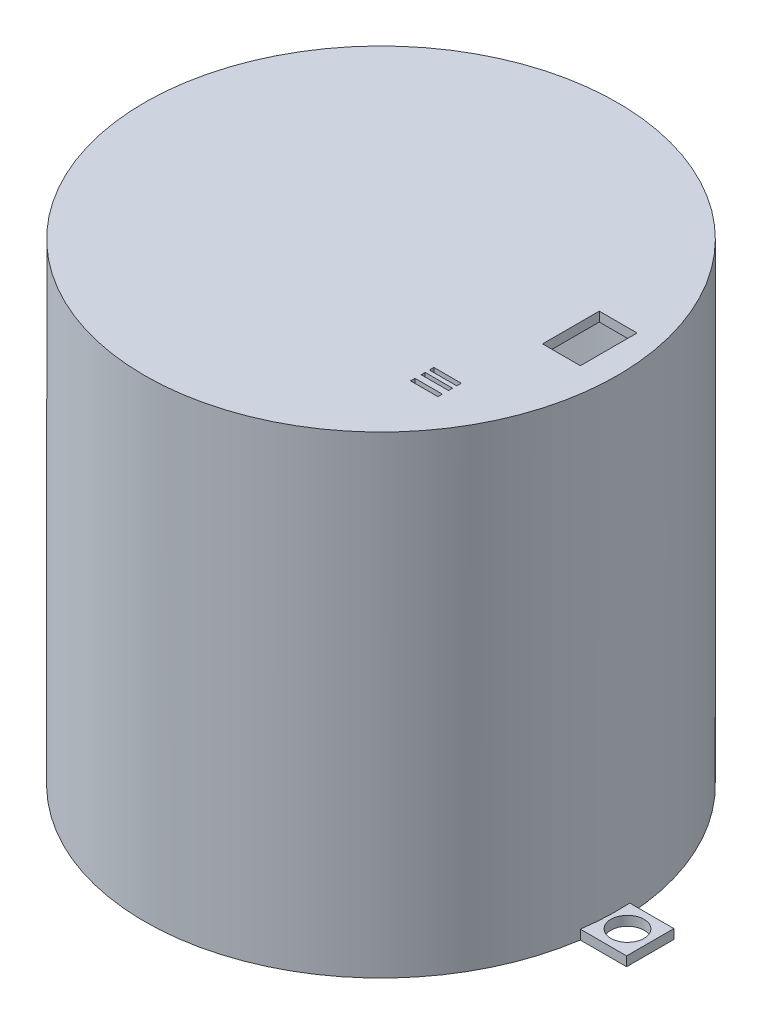
SolidWorks part; units mm, degrees
ref_plane "Front Plane" through (0, 0, 0) normal (0, 0, 1) x (1, 0, 0)
ref_plane "Top Plane" through (0, 0, 0) normal (0, 1, 0) x (1, 0, 0)
ref_plane "Right Plane" through (0, 0, 0) normal (1, 0, 0) x (0, 0, -1)
sketch "Sketch2" plane through (0, 0, 0) normal (0, 1, 0) x (1, 0, 0)
  circle A0 centre (0, 0) radius 50
  dimension "D1" = 100
extrude "Boss-Extrude1" add sketch "Sketch2" along normal blind 100
sketch "Sketch3" plane through (0, 0, 0) normal (1, 0, 0) x (0, 0, -1)
  line L0 (50, 100) -> (-50, 100) construction
  line L5 (-50, 0) -> (50, 0) construction
  line L6 (50, 0) -> (50, 100) construction
  line L7 (-30, 90) -> (30, 90)
  line L8 (-30, 90) -> (-30, 10)
  line L9 (-30, 10) -> (30, 10)
  line L10 (30, 90) -> (30, 10)
  line L11 (-50, 100) -> (-50, 0) construction
  dimension "D1" = 10
  dimension "D2" = 10
  dimension "D3" = 20
  dimension "D4" = 20
extrude "Cut-Extrude1" cut sketch "Sketch3" against normal blind 60
sketch "Sketch4" plane through (0, 0, 0) normal (-1, 0, 0) x (0, 0, 1)
  line L0 (30, 90) -> (30, 10) construction
  line L1 (-30, 10) -> (30, 10)
  line L2 (-30, 10) -> (-30, 89.6698)
  line L3 (-30, 89.6698) -> (30, 89.6698)
  line L4 (30, 10) -> (30, 89.6698)
extrude "Boss-Extrude3" add sketch "Sketch4" along normal blind 40
sketch "Sketch5" plane through (0, 0, 0) normal (0, 1, 0) x (1, 0, 0)
  circle A0 centre (0, 0) radius 38
  dimension "D1" = 76
extrude "Cut-Extrude2" cut sketch "Sketch5" along normal blind 90
sketch "Sketch6" plane through (-40, 0, 0) normal (-1, 0, 0) x (0, 0, 1)
sketch "Sketch8" plane through (-40, 0, 0) normal (-1, 0, 0) x (0, 0, 1)
  line L0 (-30, 10) -> (-30, 89.6698) construction
  line L1 (30, 89.6698) -> (-30, 89.6698)
  line L2 (30, 89.6698) -> (30, 10)
  line L3 (30, 10) -> (-30, 10)
  line L4 (-30, 89.6698) -> (-30, 10)
  line L5 (-30, 10) -> (30, 10) construction
extrude "Cut-Extrude7" cut sketch "Sketch8" against normal blind 50
sketch "Sketch10" plane through (0, 90, 0) normal (0, -1, 0) x (-1, 0, 0)
  circle A0 centre (0, 0) radius 48.6655
extrude "Cut-Extrude9" cut sketch "Sketch10" along normal blind 100
sketch "Sketch11" plane through (0, 90, 0) normal (0, -1, 0) x (1, 0, 0)
  line L1 (-40, -30) -> (-38.3188, -30)
  line L2 (-40, -30) -> (-40, 30)
  line L3 (-40, 30) -> (-38.3188, 30)
  line L4 (-38.3188, -30) -> (-38.3188, 30)
extrude "Boss-Extrude5" add sketch "Sketch11" along normal blind 80
sketch "Sketch13" plane through (0, 10, 0) normal (0, -1, 0) x (1, 0, 0)
  line L2 (-38.3188, -30) -> (-38.3188, 30) construction
  line L3 (-38.3188, 30) -> (-40, 30)
  line L4 (-38.3188, 30) -> (-38.3188, -30)
  line L5 (-38.3188, -30) -> (-40, -30)
  line L6 (-40, 30) -> (-40, -30)
  circle A1 centre (0, 0) radius 48.6655 construction
extrude "Boss-Extrude7" add sketch "Sketch13" along normal blind 10
sketch "Sketch16" plane through (0, 0, 0) normal (0, -1, 0) x (1, 0, 0)
  line L0 (-39.28, -29.0752) -> (-39.28, 29.2384)
  arc A0 (-39.28, -29.0752) -> (-39.28, 29.2384) centre (-2.0923, 0.0816) cw
extrude "Boss-Extrude8" add sketch "Sketch16" against normal blind 10
sketch "Sketch17" plane through (0, 90, 0) normal (0, -1, 0) x (1, 0, 0)
  line L0 (-38.3188, 30) -> (-38.3188, -30)
  arc A0 (-38.3188, -30) -> (-38.3188, 30) centre (0, 0) ccw
extrude "Cut-Extrude10" cut sketch "Sketch17" against normal blind 5
sketch "Sketch19" plane through (0, 95, 0) normal (0, -1, 0) x (-1, 0, 0)
  circle A0 centre (-31.4631, -20.5499) radius 8.1648
extrude "Boss-Extrude10" add sketch "Sketch19" along normal blind 5
sketch "Sketch20" plane through (0, 90, 0) normal (0, -1, 0) x (-1, 0, 0)
  circle A0 centre (-31.5379, -20.642) radius 7.0471
extrude "Cut-Extrude11" cut sketch "Sketch20" against normal blind 9
sketch "Sketch21" plane through (0, 99, 0) normal (0, -1, 0) x (1, 0, 0)
  line L1 (34.8864, 22.8527) -> (29.0984, 22.8527)
  line L2 (34.8864, 22.8527) -> (34.8864, 21.9185)
  line L3 (34.8864, 21.9185) -> (29.0984, 21.9185)
  line L4 (29.0984, 22.8527) -> (29.0984, 21.9185)
  line L5 (34.8864, 18.877) -> (29.0984, 18.877)
  line L6 (34.8864, 18.877) -> (34.8864, 17.923)
  line L7 (34.8864, 17.923) -> (29.0984, 17.923)
  line L8 (29.0984, 18.877) -> (29.0984, 17.923)
  line L9 (34.8864, 20.6036) -> (29.0984, 20.6036)
  line L10 (34.8864, 20.6036) -> (34.8864, 19.7539)
  line L11 (34.8864, 19.7539) -> (29.0984, 19.7539)
  line L12 (29.0984, 20.6036) -> (29.0984, 19.7539)
extrude "Cut-Extrude12" cut sketch "Sketch21" against normal blind 9
sketch "Sketch23" plane through (-40, 0, 0) normal (-1, 0, 0) x (0, 0, 1)
  line L1 (-25.9761, 87.4074) -> (-0.9761, 87.4074)
  line L2 (-25.9761, 87.4074) -> (-25.9761, 13.4074)
  line L3 (-25.9761, 13.4074) -> (-0.9761, 13.4074)
  line L4 (-0.9761, 87.4074) -> (-0.9761, 13.4074)
  circle A0 centre (12.4386, 73.1041) radius 2.1953
  circle A1 centre (12.4386, 51.019) radius 2.1953
  circle A2 centre (12.4386, 27.4615) radius 2.1953
  dimension "4" = 4.3906
  dimension "D1" = 25
  dimension "D2" = 74
extrude "Cut-Extrude13" cut sketch "Sketch23" against normal blind 9
sketch "Sketch24" plane through (0, 100, 0) normal (0, 1, 0) x (1, 0, 0)
  line L0 (-8.3579, -15) -> (6.6421, -15)
  line L1 (-8.0729, 20) -> (6.9271, 20)
  line L2 (-8.0729, 20) -> (-8.0729, 15)
  line L3 (-8.0729, 15) -> (6.9271, 15)
  line L4 (6.9271, 20) -> (6.9271, 15)
  line L5 (-8.3579, -15) -> (-8.3579, -20)
  line L6 (-8.3579, -20) -> (6.6421, -20)
  line L7 (6.6421, -15) -> (6.6421, -20)
  dimension "D1" = 15
  dimension "D2" = 15
  dimension "D3" = 5
  dimension "D4" = 5
  dimension "D5" = 15
  dimension "D6" = 15
extrude "Boss-Extrude11" add sketch "Sketch24" against normal blind 98
sketch "Sketch25" plane through (0, 100, 0) normal (0, 1, 0) x (1, 0, 0)
  line L5 (-29.3751, -35.8582) -> (-10.5476, -35.8582)
  line L6 (-29.3751, -35.8582) -> (-29.3751, 37.5173)
  line L7 (-29.3751, 37.5173) -> (-10.5476, 37.5173)
  line L8 (-10.5476, -35.8582) -> (-10.5476, 37.5173)
extrude "Cut-Extrude14" cut sketch "Sketch25" against normal blind 98
sketch "Sketch26" plane through (0, 100, 0) normal (0, 1, 0) x (1, 0, 0)
  line L1 (-29.3751, 37.5173) -> (-10.5476, 37.5173)
  line L2 (-29.3751, 37.5173) -> (-29.3751, -35.8582)
  line L3 (-29.3751, -35.8582) -> (-10.5476, -35.8582)
  line L4 (-10.5476, 37.5173) -> (-10.5476, -35.8582)
extrude "Boss-Extrude12" add sketch "Sketch26" against normal blind 1
sketch "Sketch27" plane through (0, 0, 0) normal (0, -1, 0) x (1, 0, 0)
  line L0 (49.2237, 7.3146) -> (59.2536, 7.3146)
  line L1 (-59.2536, 5.6794) -> (-49.2237, 5.6794)
  line L2 (-59.2536, 5.6794) -> (-59.2536, -4.3206)
  line L3 (-59.2536, -4.3206) -> (-49.2237, -4.3206)
  line L4 (-49.2237, 5.6794) -> (-49.2237, -4.3206)
  line L5 (49.2237, 7.3146) -> (49.2237, -2.6854)
  line L6 (49.2237, -2.6854) -> (59.2536, -2.6854)
  line L7 (59.2536, 7.3146) -> (59.2536, -2.6854)
  dimension "D1" = 10
extrude "Boss-Extrude13" add sketch "Sketch27" against normal blind 2
sketch "Sketch28" plane through (0, 0, 0) normal (0, -1, 0) x (1, 0, 0)
  line L0 (-59.2536, 5.6794) -> (-59.2536, -4.3206) construction
  circle A0 centre (-54.0536, 0) radius 3.5
  circle A1 centre (54.3961, 2.2722) radius 3.5
  dimension "D1" = 7
  dimension "D2" = 5.2
extrude "Cut-Extrude15" cut sketch "Sketch28" against normal blind 2
sketch "Sketch29" plane through (0, 0, 0) normal (0, -1, 0) x (1, 0, 0)
  line L0 (-29.3751, -37.5173) -> (-29.3751, 35.8582) construction
  line L1 (-29.3751, -22.8373) -> (29.1639, -22.8373)
  line L2 (-29.3751, -22.8373) -> (-29.3751, -37.5173)
  line L3 (-29.3751, -37.5173) -> (29.1639, -37.5173)
  line L4 (29.1639, -22.8373) -> (29.1639, -37.5173)
  dimension "D1" = 58.5389
extrude "Cut-Extrude16" cut sketch "Sketch29" against normal blind 98
sketch "Sketch30" plane through (0, 0, 0) normal (0, -1, 0) x (1, 0, 0)
  line L0 (29.1639, -37.5173) -> (29.1639, -22.8373) construction
  line L1 (29.1639, -22.8373) -> (8.9498, -22.8373)
  line L2 (29.1639, -22.8373) -> (29.1639, 11.4187)
  line L3 (29.1639, 11.4187) -> (8.9498, 11.4187)
  line L4 (8.9498, -22.8373) -> (8.9498, 11.4187)
extrude "Cut-Extrude17" cut sketch "Sketch30" against normal blind 98
sketch "Sketch33" plane through (0, 95, 0) normal (0, -1, 0) x (1, 0, 0)
  line L1 (36.2859, 2.1244) -> (44.2859, 2.1244)
  line L2 (36.2859, 2.1244) -> (36.2859, -9.8756)
  line L3 (36.2859, -9.8756) -> (44.2859, -9.8756)
  line L4 (44.2859, 2.1244) -> (44.2859, -9.8756)
  dimension "D1" = 12
  dimension "D2" = 8
extrude "Cut-Extrude19" cut sketch "Sketch33" against normal blind 98
sketch "Sketch34" plane through (0, 0, 0) normal (0, -1, 0) x (1, 0, 0)
  line L1 (29.1639, 11.4187) -> (45.5203, 11.4187)
  line L2 (29.1639, 11.4187) -> (29.1639, -14.6591)
  line L3 (29.1639, -14.6591) -> (45.5203, -14.6591)
  line L4 (45.5203, 11.4187) -> (45.5203, -14.6591)
extrude "Cut-Extrude20" cut sketch "Sketch34" against normal blind 98
sketch "Sketch35" plane through (0, 98, 0) normal (0, -1, 0) x (1, 0, 0)
  line L0 (8.9498, 11.4187) -> (8.9498, -22.8373) construction
  line L1 (-10.4955, 8.4657) -> (8.9498, 8.4657)
  line L2 (-10.4955, 8.4657) -> (-10.4955, -11.3053)
  line L3 (-10.4955, -11.3053) -> (8.9498, -11.3053)
  line L4 (8.9498, 8.4657) -> (8.9498, -11.3053)
extrude "Cut-Extrude21" cut sketch "Sketch35" along normal blind 10
sketch "Sketch36" plane through (0, 98, 0) normal (0, -1, 0) x (1, 0, 0)
  line L35 (-10.5476, -37.5173) -> (29.1639, -37.5173) construction
  line L36 (-28.7067, 35.3106) -> (-8.7175, 35.3106)
  line L37 (-28.7067, 35.3106) -> (-28.7067, -37.5173)
  line L38 (-28.7067, -37.5173) -> (-8.7175, -37.5173)
  line L39 (-8.7175, 35.3106) -> (-8.7175, -37.5173)
extrude "Cut-Extrude24" cut sketch "Sketch36" along normal blind 10
sketch "Sketch37" plane through (0, 98, 0) normal (0, -1, 0) x (1, 0, 0)
  line L1 (-9.8861, 14.4489) -> (21.9016, 14.4489)
  line L2 (-9.8861, 14.4489) -> (-9.8861, 4.1065)
  line L3 (-9.8861, 4.1065) -> (21.9016, 4.1065)
  line L4 (21.9016, 14.4489) -> (21.9016, 4.1065)
extrude "Cut-Extrude26" cut sketch "Sketch37" along normal blind 10
sketch "Sketch38" plane through (0, 95, 0) normal (0, -1, 0) x (-1, 0, 0)
  line L16 (9.8383, 10.423) -> (-11.063, 10.423)
  line L17 (9.8383, 10.423) -> (9.8383, 14.6261)
  line L18 (9.8383, 14.6261) -> (-11.063, 14.6261)
  line L19 (-11.063, 10.423) -> (-11.063, 14.6261)
  line L20 (9.8383, 21.1202) -> (-11.063, 21.1202)
  line L21 (9.8383, 21.1202) -> (9.8383, 24.9403)
  line L22 (9.8383, 24.9403) -> (-11.063, 24.9403)
  line L23 (-11.063, 21.1202) -> (-11.063, 24.9403)
  line L24 (8.7175, -35.3106) -> (-21.8163, -35.3106)
  line L25 (8.7175, -35.3106) -> (8.7175, -21.2527)
  line L26 (8.7175, -21.2527) -> (-21.8163, -21.2527)
  line L27 (-21.8163, -35.3106) -> (-21.8163, -21.2527)
extrude "Cut-Extrude32" cut sketch "Sketch38" against normal blind 2
sketch "Sketch39" plane through (0, 97, 0) normal (0, -1, 0) x (1, 0, 0)
  line L1 (-8.7175, 35.3106) -> (21.8163, 35.3106)
  line L2 (-8.7175, 35.3106) -> (-8.7175, 21.2527)
  line L3 (-8.7175, 21.2527) -> (21.8163, 21.2527)
  line L4 (21.8163, 35.3106) -> (21.8163, 21.2527)
extrude "Cut-Extrude33" cut sketch "Sketch39" against normal blind 1
sketch "Sketch40" plane through (0, 99, 0) normal (0, -1, 0) x (1, 0, 0)
  line L0 (-10.5476, -37.5173) -> (29.1639, -37.5173) construction
  line L1 (-29.3751, 35.8582) -> (-8.8215, 35.8582)
  line L2 (-29.3751, 35.8582) -> (-29.3751, -37.5173)
  line L3 (-29.3751, -37.5173) -> (-8.8215, -37.5173)
  line L4 (-8.8215, 35.8582) -> (-8.8215, -37.5173)
extrude "Boss-Extrude14" add sketch "Sketch40" along normal blind 1
sketch "Sketch41" plane through (0, 95, 0) normal (0, -1, 0) x (1, 0, 0)
  line L1 (-10.5476, 35.8582) -> (22.0737, 35.8582)
  line L2 (-10.5476, 35.8582) -> (-10.5476, 20.1152)
  line L3 (-10.5476, 20.1152) -> (22.0737, 20.1152)
  line L4 (22.0737, 35.8582) -> (22.0737, 20.1152)
extrude "Cut-Extrude34" cut sketch "Sketch41" against normal blind 3
sketch "Sketch42" plane through (0, 95, 0) normal (0, -1, 0) x (1, 0, 0)
  line L0 (-8.7175, 20.1152) -> (22.0737, 20.1152) construction
  line L1 (7.7568, 20.1152) -> (21.9016, 20.1152)
  line L2 (7.7568, 20.1152) -> (7.7568, 11.4187)
  line L3 (7.7568, 11.4187) -> (21.9016, 11.4187)
  line L4 (21.9016, 20.1152) -> (21.9016, 11.4187)
extrude "Cut-Extrude35" cut sketch "Sketch42" against normal blind 3
sketch "Sketch43" plane through (0, 95, 0) normal (0, -1, 0) x (1, 0, 0)
  line L0 (-29.3751, 35.8582) -> (-29.3751, -37.5173) construction
  line L1 (-29.3751, 35.8582) -> (30.2698, 35.8582)
  line L2 (-29.3751, 35.8582) -> (-29.3751, 38.1061)
  line L3 (-29.3751, 38.1061) -> (30.2698, 38.1061)
  line L4 (30.2698, 35.8582) -> (30.2698, 38.1061)
  line L5 (-29.3751, 35.8582) -> (-29.3751, -37.5173) construction
  arc A0 (-38.3188, -30) -> (-38.3188, 30) centre (0, 0) ccw construction
extrude "Cut-Extrude36" cut sketch "Sketch43" against normal blind 3
sketch "Sketch44" plane through (0, 97, 0) normal (0, -1, 0) x (1, 0, 0)
  line L2 (-8.7175, -11.3053) -> (-8.7175, -14.6261)
  line L9 (38.925, -24.3914) -> (24.1719, -24.3914)
  line L14 (38.925, -24.3914) -> (38.925, -12.7138)
  line L19 (-8.7175, -11.3053) -> (8.9498, -11.3053)
  line L21 (-8.7175, -14.6261) -> (8.9498, -14.6261)
  line L22 (8.9498, -11.3053) -> (8.9498, -14.6261)
  line L23 (38.925, -12.7138) -> (24.1719, -12.7138)
  line L24 (24.1719, -24.3914) -> (24.1719, -12.7138)
extrude "Cut-Extrude38" cut sketch "Sketch44" along normal blind 3
sketch "Sketch46" plane through (0, 97, 0) normal (0, -1, 0) x (1, 0, 0)
  line L1 (-8.7175, -11.3053) -> (8.9498, -11.3053)
  line L2 (-8.7175, -11.3053) -> (-8.7175, -14.6261)
  line L3 (-8.7175, -14.6261) -> (8.9498, -14.6261)
  line L4 (8.9498, -11.3053) -> (8.9498, -14.6261)
extrude "Cut-Extrude40" cut sketch "Sketch46" against normal blind 1
sketch "Sketch47" plane through (0, 95, 0) normal (0, -1, 0) x (1, 0, 0)
  line L0 (8.9498, -22.8373) -> (-8.7175, -22.8373) construction
  line L1 (8.9498, -14.6261) -> (7.2487, -14.6261)
  line L2 (8.9498, -14.6261) -> (8.9498, -22.8373)
  line L3 (8.9498, -22.8373) -> (7.2487, -22.8373)
  line L4 (7.2487, -14.6261) -> (7.2487, -22.8373)
extrude "Cut-Extrude41" cut sketch "Sketch47" against normal blind 3
sketch "Sketch48" plane through (0, 95, 0) normal (0, -1, 0) x (1, 0, 0)
  line L0 (-8.7175, -14.6261) -> (-8.7175, -21.1202) construction
  line L1 (-8.7175, -20.3589) -> (7.2487, -20.3589)
  line L2 (-8.7175, -20.3589) -> (-8.7175, -22.8373)
  line L3 (-8.7175, -22.8373) -> (7.2487, -22.8373)
  line L4 (7.2487, -20.3589) -> (7.2487, -22.8373)
  line L5 (7.2487, -14.6261) -> (7.2487, -22.8373) construction
  line L6 (7.2487, -21.1202) -> (7.2487, -22.8373) construction
extrude "Cut-Extrude42" cut sketch "Sketch48" against normal blind 3
sketch "Sketch49" plane through (0, 95, 0) normal (0, -1, 0) x (1, 0, 0)
  line L1 (-38.3188, 30) -> (-27.8452, 30)
  line L2 (-38.3188, 30) -> (-38.3188, -30)
  line L3 (-38.3188, -30) -> (-27.8452, -30)
  line L4 (-27.8452, 30) -> (-27.8452, -30)
extrude "Cut-Extrude43" cut sketch "Sketch49" against normal blind 3
sketch "Sketch50" plane through (0, 95, 0) normal (0, -1, 0) x (1, 0, 0)
  line L1 (22.0737, 35.8582) -> (31.5515, 35.8582)
  line L2 (22.0737, 35.8582) -> (22.0737, 29.8738)
  line L3 (22.0737, 29.8738) -> (31.5515, 29.8738)
  line L4 (31.5515, 35.8582) -> (31.5515, 29.8738)
  line L5 (22.0737, 29.8738) -> (21.0336, 29.8738)
  line L6 (22.0737, 29.8738) -> (22.0737, 10.9415)
  line L7 (22.0737, 10.9415) -> (21.0336, 10.9415)
  line L8 (21.0336, 29.8738) -> (21.0336, 10.9415)
  line M8 (30.2698, 35.8582) -> (22.0737, 35.8582)
  line M9 (22.0737, 35.8582) -> (22.0737, 20.1152)
  line M10 (22.0737, 20.1152) -> (21.9016, 20.1152)
  line M11 (21.9016, 20.1152) -> (21.9016, 11.4187)
  line M12 (21.9016, 11.4187) -> (45.5203, 11.4187)
extrude "Cut-Extrude44" cut sketch "Sketch50" against normal blind 3 contours L5 L8 L7 L6 M12 M11 M10 M9 | L4 L1 L3 M8 M9
sketch "Sketch51" plane through (0, 95, 0) normal (0, -1, 0) x (1, 0, 0)
  line L5 (19.2323, 31.2232) -> (22.5475, 31.2232)
  line L6 (19.2323, 31.2232) -> (19.2323, 9.0847)
  line L7 (19.2323, 9.0847) -> (22.5475, 9.0847)
  line L8 (22.5475, 31.2232) -> (22.5475, 9.0847)
extrude "Cut-Extrude45" cut sketch "Sketch51" against normal blind 3
sketch "Sketch53" plane through (0, 95, 0) normal (0, -1, 0) x (1, 0, 0)
  line L1 (-38.3188, -30) -> (-29.3751, -30)
  line L2 (-29.3751, -30) -> (-29.3751, -37.5173)
  line L3 (-29.3751, -37.5173) -> (-29.685, -38.5634)
  arc A2 (-38.3188, -30) -> (-29.685, -38.5634) centre (0, 0) ccw
  arc A3 (-38.3188, -30) -> (30.2698, 38.1061) centre (0, 0) ccw construction
extrude "Cut-Extrude52" cut sketch "Sketch53" against normal blind 3
sketch "Sketch55" plane through (0, 95, 0) normal (0, -1, 0) x (-1, 0, 0)
  line L0 (-30.2698, -38.1061) -> (29.3751, -38.1061) construction
  line L1 (38.3188, -30) -> (29.3751, -30)
  line L2 (29.3751, -30) -> (29.3751, -38.1061)
  line L3 (29.3751, -38.1061) -> (-30.2698, -38.1061)
  arc A0 (38.3188, -30) -> (-30.2698, -38.1061) centre (0, 0) cw
  arc A2 (-30.2698, -38.1061) -> (38.3188, -30) centre (0, 0) ccw construction
extrude "Cut-Extrude57" cut sketch "Sketch55" against normal blind 3
sketch "Sketch56" plane through (0, 95, 0) normal (0, -1, 0) x (-1, 0, 0)
  line L0 (-38.6367, -29.5895) -> (-31.5515, -29.8738)
  line L1 (-31.5515, -29.8738) -> (-31.5515, -35.8582)
  line L2 (-31.5515, -35.8582) -> (-30.2698, -35.8582)
  line L3 (-30.2698, -35.8582) -> (-30.2698, -38.1061)
  arc A0 (-30.2698, -38.1061) -> (-38.6367, -29.5895) centre (0, 0) cw
  arc A1 (29.685, 38.5634) -> (-30.2698, -38.1061) centre (0, 0) ccw construction
extrude "Cut-Extrude58" cut sketch "Sketch56" against normal blind 3
sketch "Sketch57" plane through (0, 95, 0) normal (0, -1, 0) x (-1, 0, 0)
  line L0 (-46.3337, 14.8837) -> (-45.5203, 14.6591)
  line L1 (-45.5203, 14.6591) -> (-45.5203, -11.4187)
  line L2 (-45.5203, -11.4187) -> (-47.2878, -11.4975)
  arc A0 (-47.2878, -11.4975) -> (-46.3337, 14.8837) centre (0, 0) cw
  arc A1 (29.685, 38.5634) -> (-38.6367, -29.5895) centre (0, 0) ccw construction
extrude "Cut-Extrude59" cut sketch "Sketch57" against normal blind 3
sketch "Sketch58" plane through (0, 95, 0) normal (0, -1, 0) x (-1, 0, 0)
  line L0 (-38.9446, 29.183) -> (-38.925, 14.6591)
  line L1 (-38.925, 14.6591) -> (-45.5203, 14.6591)
  line L2 (-45.5203, 14.6591) -> (-46.3337, 14.8837)
  arc A0 (-46.3337, 14.8837) -> (-38.9446, 29.183) centre (0, 0) cw
  arc A1 (29.685, 38.5634) -> (-46.3337, 14.8837) centre (0, 0) ccw construction
extrude "Cut-Extrude60" cut sketch "Sketch58" against normal blind 3
sketch "Sketch59" plane through (0, 97, 0) normal (0, -1, 0) x (1, 0, 0)
  line L1 (28.3881, -6.9602) -> (40.1118, -6.9602)
  line L2 (28.3881, -6.9602) -> (28.3881, -26.4321)
  line L3 (28.3881, -26.4321) -> (40.1118, -26.4321)
  line L4 (40.1118, -6.9602) -> (40.1118, -26.4321)
extrude "Cut-Extrude63" cut sketch "Sketch59" against normal blind 1
sketch "Sketch60" plane through (0, 95, 0) normal (0, -1, 0) x (1, 0, 0)
  line L1 (38.9446, -29.183) -> (27.5275, -29.183)
  line L2 (38.9446, -29.183) -> (38.9446, -11.7376)
  line L3 (38.9446, -11.7376) -> (27.5275, -11.7376)
  line L4 (27.5275, -29.183) -> (27.5275, -11.7376)
extrude "Cut-Extrude65" cut sketch "Sketch60" against normal blind 3
sketch "Sketch61" plane through (0, 95, 0) normal (0, -1, 0) x (-1, 0, 0)
  line L0 (29.685, 38.5634) -> (29.3906, 37.5697)
  line L1 (29.685, 38.5634) -> (29.3751, 37.5173) construction
  line L2 (29.3906, 37.5697) -> (-29.1639, 37.5173)
  line L3 (-29.1639, 37.5173) -> (-29.1639, 29.183)
  line L4 (-29.1639, 29.183) -> (-38.9446, 29.183)
  arc A0 (-38.9446, 29.183) -> (29.685, 38.5634) centre (0, 0) cw
extrude "Cut-Extrude66" cut sketch "Sketch61" against normal blind 3
